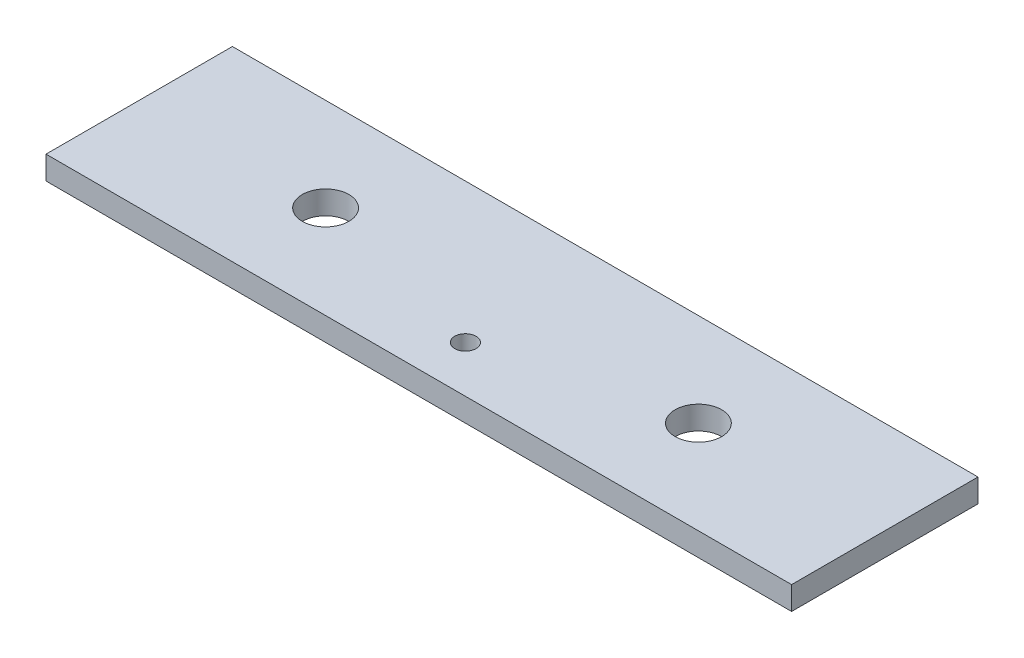
SolidWorks part; units mm, degrees
ref_plane "Front Plane" through (0, 0, 0) normal (0, 0, 1) x (1, 0, 0)
ref_plane "Top Plane" through (0, 0, 0) normal (0, 1, 0) x (1, 0, 0)
ref_plane "Right Plane" through (0, 0, 0) normal (1, 0, 0) x (0, 0, -1)
sketch "Sketch1" plane through (0, 0, 0) normal (0, 1, 0) x (1, 0, 0)
  line L1 (0, 0) -> (101.6, 0)
  line L2 (0, 0) -> (0, 25.4)
  line L3 (0, 25.4) -> (101.6, 25.4)
  line L4 (101.6, 0) -> (101.6, 25.4)
  dimension "D1" = 25.4
  dimension "D2" = 101.6
extrude "Boss-Extrude1" add sketch "Sketch1" along normal blind 3.175
sketch "Sketch2" plane through (0, 3.175, 0) normal (0, 1, 0) x (1, 0, 0)
  line L0 (0, 0) -> (101.6, 0) construction
  line L1 (101.6, 0) -> (101.6, 25.4) construction
  circle A0 centre (50.8, 6.35) radius 1.4605
  circle A1 centre (25.4, 12.7) radius 3.175
  circle A2 centre (76.2, 12.7) radius 3.175
  dimension "D1" = 2.921
  dimension "D2" = 6.35
  dimension "D3" = 50.8
  dimension "D4" = 6.35
  dimension "D5" = 6.35
  dimension "D6" = 50.8
  dimension "D7" = 25.4
  dimension "D8" = 12.7
  dimension "D9" = 12.7
extrude "Cut-Extrude1" cut sketch "Sketch2" against normal through all
